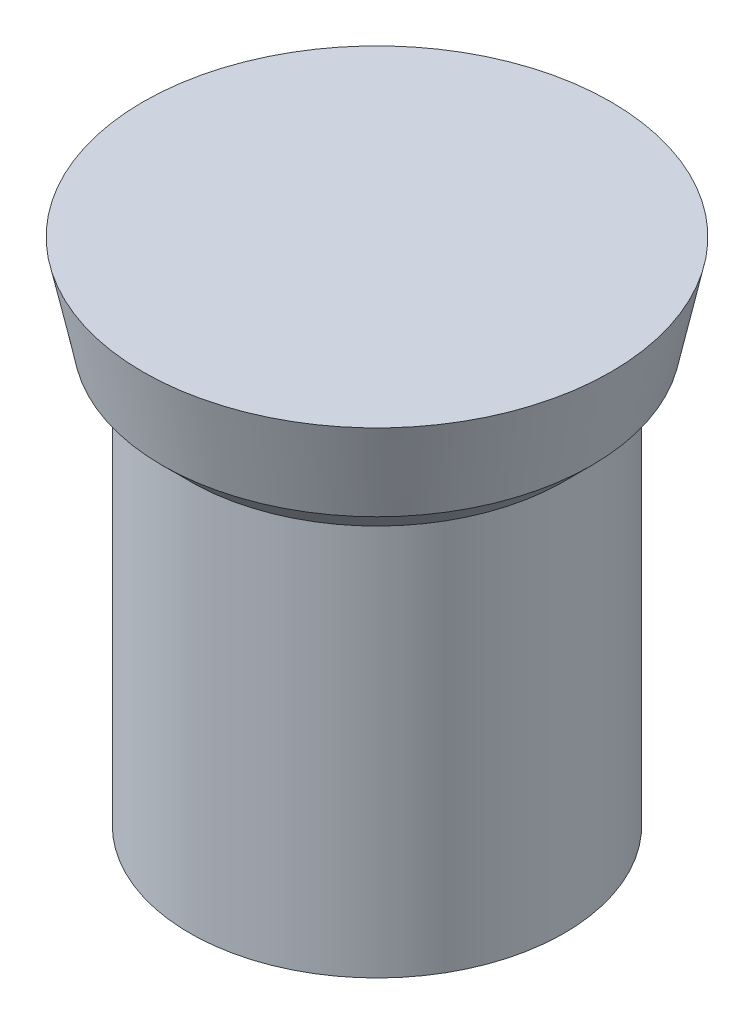
SolidWorks part; units mm, degrees
ref_plane "Front Plane" through (0, 0, 0) normal (0, 0, 1) x (1, 0, 0)
ref_plane "Top Plane" through (0, 0, 0) normal (0, 1, 0) x (1, 0, 0)
ref_plane "Right Plane" through (0, 0, 0) normal (1, 0, 0) x (0, 0, -1)
sketch "Sketch1" plane through (0, 0, 0) normal (0, 0, 1) x (1, 0, 0)
  line L0 (0, 0) -> (0, 22.6586) construction
  line L1 (0, 0) -> (0, 13.5)
  line L2 (0, 13.5) -> (6.2, 13.5)
  line L3 (6.2, 13.5) -> (5.6899, 11.1)
  line L4 (6.2, 13.5) -> (6.2, 5.3674) construction
  line L5 (5.6899, 11.1) -> (4.9609, 10.3711)
  line L6 (4.9609, 0) -> (4.9609, 10.3711)
  line L7 (5.5562, 13.5) -> (5.5563, 2) construction
  line L8 (0, 0) -> (4.9609, 0)
  line L9 (5.5563, 2) -> (0, 2) construction
  dimension "D1" = 12.4
  dimension "D2" = 12
  dimension "D3" = 2.4
  dimension "D4" = 2
  dimension "D5" = 45
  dimension "D6" = 9.9219
  dimension "D7" = 11.5
  dimension "D8" = 11.1125
revolve "Revolve1" add sketch "Sketch1" angle 360 about L0
